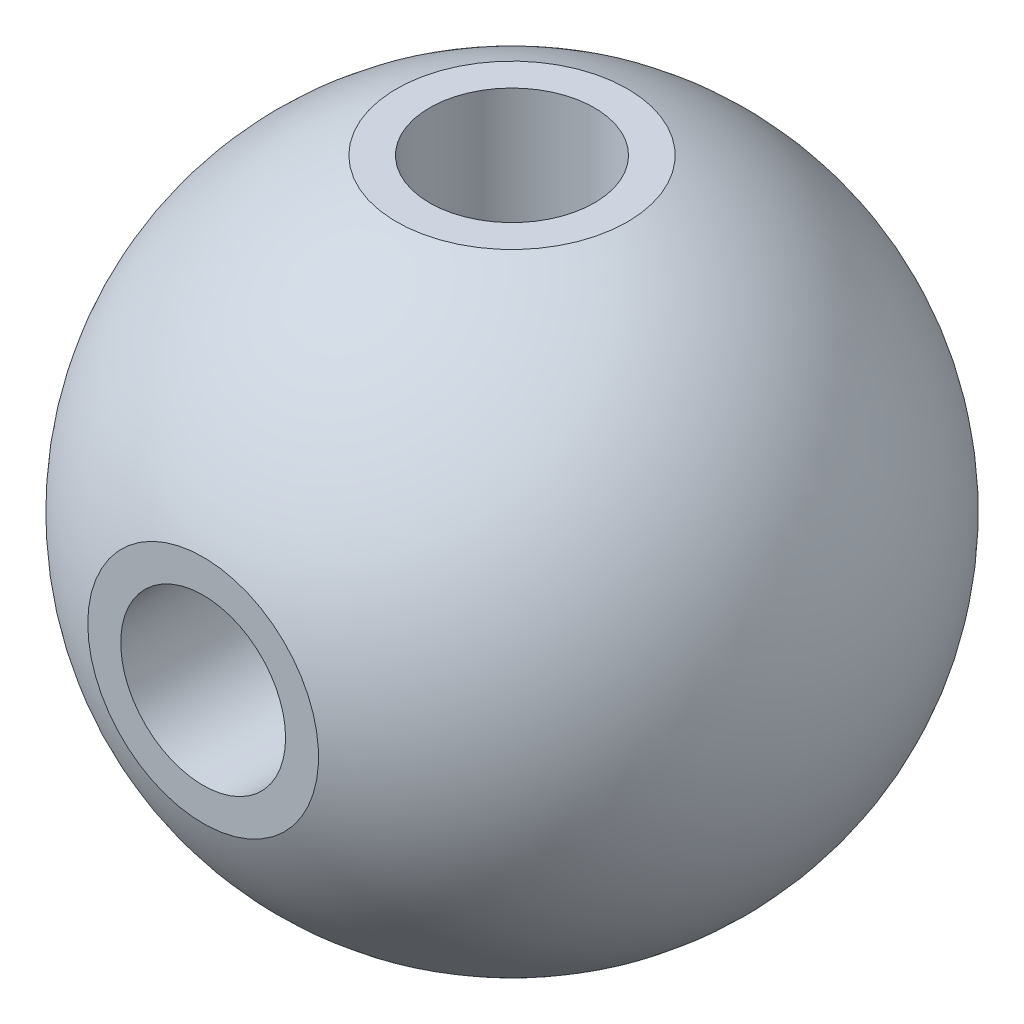
SolidWorks part; units mm, degrees
ref_plane "Front Plane" through (0, 0, 0) normal (0, 0, 1) x (1, 0, 0)
ref_plane "Top Plane" through (0, 0, 0) normal (0, 1, 0) x (1, 0, 0)
ref_plane "Right Plane" through (0, 0, 0) normal (1, 0, 0) x (0, 0, -1)
sketch "Sketch2" plane through (0, 0, 0) normal (0, 0, 1) x (1, 0, 0)
  line L0 (0, 0) -> (0, 12.7) construction
  line L3 (0, 12.7) -> (0, -12.7)
  line L4 (0, 0) -> (0, 12.7) construction
  arc A0 (0, -12.7) -> (0, 12.7) centre (0, 0) ccw
  dimension "D1" = 25.4
revolve "Revolve2" add sketch "Sketch2" angle 360 about L0
sketch "Sketch3" plane through (0, 0, 0) normal (0, 0, 1) x (1, 0, 0)
  circle A0 centre (0, 0) radius 4.445
  dimension "D1" = 8.89
extrude "Cut-Extrude1" cut sketch "Sketch3" along normal blind 2.54 from surface at 11.8967
sketch "Sketch4" plane through (0, 0, 11.8967) normal (0, 0, 1) x (1, 0, 0)
  circle A0 centre (0, 0) radius 3.175
  dimension "D1" = 6.35
extrude "Cut-Extrude2" cut sketch "Sketch4" against normal blind 7.62
mirror "Mirror1" about plane through (0, 0, 0) normal (0, 0, 1) of "Cut-Extrude2", "Cut-Extrude1"
sketch "Sketch5" plane through (0, 0, 0) normal (0, 1, 0) x (1, 0, 0)
  circle A0 centre (0, 0) radius 4.445
  dimension "D1" = 8.89
extrude "Cut-Extrude3" cut sketch "Sketch5" along normal blind 7.62 from surface at 11.8967 starting at face at (4.445, 0, -11.8967)
sketch "Sketch6" plane through (0, 11.8967, 0) normal (0, 1, 0) x (1, 0, 0)
  circle A0 centre (0, 0) radius 3.175
  dimension "D1" = 6.35
extrude "Cut-Extrude4" cut sketch "Sketch6" against normal blind 7.62
